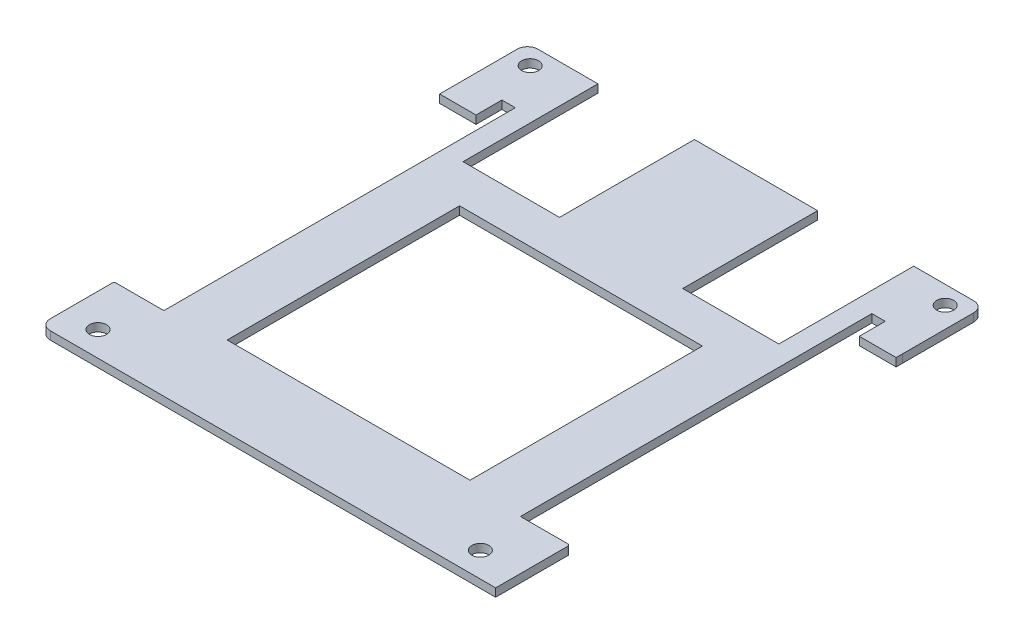
SolidWorks part; units mm, degrees
material "Copper"
ref_plane "Front Plane" through (0, 0, 0) normal (0, 0, 1) x (1, 0, 0)
ref_plane "Top Plane" through (0, 0, 0) normal (0, 1, 0) x (1, 0, 0)
ref_plane "Right Plane" through (0, 0, 0) normal (1, 0, 0) x (0, 0, -1)
sketch "Sketch1" plane through (0, 0, 0) normal (0, 1, 0) x (1, 0, 0)
  line L0 (-44, 45) -> (-44, 29.1624)
  line L1 (-43.6121, 28.7745) -> (-33.2119, 28.7745)
  line L2 (-42, 47) -> (42, 47)
  line L3 (44, 45) -> (44, 31.284)
  line L4 (32.8228, 27.7745) -> (32.8228, -30.4694)
  line L5 (26.2188, 17.9319) -> (-33.6927, 17.9319) construction
  line L6 (33.8228, 28.7745) -> (43.6111, 28.7745)
  line L7 (43.8497, -38.27) -> (43.8497, -47)
  line L8 (42.7059, -47) -> (-42, -47)
  line L9 (-44, -45) -> (-44, -38.977)
  line L10 (-32.824, 28.3866) -> (-32.824, -32.3056)
  line L11 (33.824, -32.6935) -> (36.0988, -32.6935)
  line L12 (23.409, -31.5) -> (-23.409, -31.5)
  line L13 (-23.409, -31.5) -> (-23.409, 13.2954)
  line L14 (-23.409, 13.2954) -> (-12.909, 13.2954)
  line L15 (-12.909, 13.2954) -> (-12.909, 25.9954)
  line L16 (-12.909, 25.9954) -> (12.909, 25.9954)
  line L17 (12.909, 25.9954) -> (12.909, 13.2954)
  line L18 (12.909, 13.2954) -> (23.409, 13.2954)
  line L19 (23.409, 13.2954) -> (23.409, -31.5)
  line L20 (43.8497, -38.27) -> (43.8497, -33.0814)
  line L21 (43.4618, -32.6935) -> (36.0988, -32.6935)
  line L22 (43.8497, -47) -> (42.7059, -47)
  line L23 (-44, 28.7745) -> (52.9697, 28.7745) construction
  line L24 (44, 31.284) -> (43.999, 29.1622)
  line L25 (-33.2119, -32.6935) -> (-36.1, -32.6935)
  line L26 (-44, -38.977) -> (-44, -33.0814)
  line L27 (-43.6121, -32.6935) -> (-36.1, -32.6935)
  line L28 (32.8228, -30.4694) -> (32.8228, -32.6935)
  line L29 (32.8228, -32.6935) -> (33.824, -32.6935)
  circle A0 centre (40, 43.5) radius 1.6383
  circle A1 centre (-40, 43.5) radius 1.6383
  circle A2 centre (-37.6, -42.2) radius 1.6383
  circle A3 centre (36.1, -42.2) radius 1.6383
  arc A5 (-42, 47) -> (-44, 45) centre (-42, 45) ccw
  arc A6 (44, 45) -> (42, 47) centre (42, 45) ccw
  arc A7 (-32.824, -32.3056) -> (-33.2119, -32.6935) centre (-33.2119, -32.3056) cw
  arc A10 (-33.2119, 28.7745) -> (-32.824, 28.3866) centre (-33.2119, 28.3866) cw
  arc A11 (-44, -45) -> (-42, -47) centre (-42, -45) ccw
  arc A12 (-44, 29.1624) -> (-43.6121, 28.7745) centre (-43.6121, 29.1624) ccw
  arc A13 (43.999, 29.1622) -> (43.6111, 28.7745) centre (43.6111, 29.1624) cw
  arc A14 (43.8497, -33.0814) -> (43.4618, -32.6935) centre (43.4618, -33.0814) ccw
  arc A15 (-44, -33.0814) -> (-43.6121, -32.6935) centre (-43.6121, -33.0814) cw
  arc A16 (33.8228, 28.7745) -> (32.8228, 27.7745) centre (33.8228, 27.7745) ccw
  point P27 (32.8228, -32.6935)
  point P51 (-32.824, -32.6935)
  point P54 (-32.824, 28.7745)
  point P60 (43.9988, 28.7745)
  point P67 (32.8228, 28.7745)
  dimension "D24" = 61.468
  dimension "D3" = 80
  dimension "D8" = 3.2766
  dimension "D22" = 1
  dimension "D2" = 6.4
  dimension "D4" = 44.7954
  dimension "D5" = 12.7
  dimension "D6" = 44.7954
  dimension "D7" = 3.5
  dimension "D9" = 4
  dimension "D10" = 3.5
  dimension "D11" = 85.7
  dimension "D12" = 85.7
  dimension "D13" = 21.0046
  dimension "D14" = 11.176
  dimension "D15" = 84
  dimension "D16" = 25.818
  dimension "D17" = 12.7
  dimension "D18" = 46.818
  dimension "D19" = 10.5
  dimension "D20" = 10.5
  dimension "D21" = 73.7
  dimension "D23" = 13.716
  dimension "D26" = 6.604
  dimension "D29" = 11.176
  dimension "D30" = 61.468
  dimension "D31" = 3.276
  dimension "D32" = 3.276
extrude "Boss-Extrude1" add sketch "Sketch1" along normal blind 1.575
sketch "Sketch2" plane through (0, 1.575, 0) normal (0, 1, 0) x (1, 0, 0)
  line L0 (-12.909, 19.06) -> (-30.435, 19.06)
  line L1 (42, 47) -> (-42, 47) construction
  line L2 (-12.909, 25.9954) -> (12.909, 25.9954) construction
  line L3 (-30.435, 47) -> (30.435, 47)
  line L4 (12.909, 13.2954) -> (12.909, 25.9954) construction
  line L5 (12.909, 19.06) -> (30.435, 19.06)
  line L6 (30.435, 19.06) -> (30.435, 47)
  line L7 (0, 47) -> (0, -47) construction
  line L8 (-42, -47) -> (43.8497, -47) construction
  line L9 (-12.909, 25.9954) -> (-12.909, 19.06)
  line L10 (-30.435, 19.06) -> (-30.435, 47)
  line L11 (12.909, 25.9954) -> (12.909, 19.06)
  line L13 (-12.909, 25.9954) -> (12.909, 25.9954)
  dimension "D1" = 27.94
  dimension "D2" = 17.526
extrude "Cut-Extrude1" cut sketch "Sketch2" against normal blind 2.54
sketch "Sketch16" plane through (0, 1.575, 0) normal (0, 1, 0) x (1, 0, 0)
  line L0 (-42, 47) -> (42, 47) construction
  line L1 (12.909, 19.06) -> (12.909, 13.2954)
  line L2 (12.909, 13.2954) -> (-12.909, 13.2954)
  line L3 (-11.8389, 47) -> (-11.8389, 21)
  line L4 (-30.435, 21) -> (-11.8389, 21)
  line L5 (11.909, 21) -> (11.909, 47)
  line L6 (11.909, 47) -> (-11.8389, 47)
  line L7 (-30.435, 47) -> (-30.435, 19.06) construction
  line L9 (-12.909, 19.06) -> (-12.909, 13.2954)
  line L10 (-30.435, 47) -> (-42, 47) construction
  line L11 (11.909, 21) -> (30.435, 21)
  line L12 (30.435, 19.06) -> (30.435, 47) construction
  line L13 (30.435, 21) -> (30.435, 19.06)
  line L14 (30.435, 19.06) -> (12.909, 19.06)
  line L15 (-30.435, 21) -> (-30.435, 19.06)
  line L16 (-30.435, 19.06) -> (-12.909, 19.06)
  dimension "D1" = 26
extrude "Cutouts for Thruster Heads" add sketch "Sketch16" against normal blind 1.575
sketch "Sketch17" plane through (0, 1.575, 0) normal (0, 1, 0) x (1, 0, 0)
  line L2 (-42.6204, -10.5244) -> (-42.6204, -23.1918)
  line L3 (-42.6204, -23.1918) -> (43.1801, -23.1918)
  line L4 (43.1801, -10.5244) -> (43.1801, -23.1918)
  line L6 (-42.6204, -10.5244) -> (-42.6204, 5.0143)
  line L7 (-42.6204, 5.0143) -> (43.1801, 5.0143)
  line L8 (43.1801, -10.5244) -> (43.1801, 5.0143)
sketch "Sketch18" plane through (0, 1.575, 0) normal (0, 1, 0) x (1, 0, 0)
  line L1 (33.4307, -29.0671) -> (45.3514, -29.0671)
  line L2 (33.4307, -29.0671) -> (33.4307, -32.653)
  line L3 (33.4307, -32.653) -> (45.3514, -32.653)
  line L4 (45.3514, -29.0671) -> (45.3514, -32.653)
  dimension "D1" = 14.347
  dimension "D2" = 10.419
sketch "Sketch21" [suppressed] plane through (0, 1.575, 0) normal (0, 1, 0) x (1, 0, 0)
  line L0 (-32.824, 28.3866) -> (-32.824, -32.3056) construction
  line L1 (-32.824, -23.1918) -> (32.8228, -23.1918)
  line L2 (-32.824, -23.1918) -> (-32.824, -25.8658)
  line L3 (-32.824, -25.8658) -> (32.8228, -25.8658)
  line L4 (32.8228, -23.1918) -> (32.8228, -25.8658)
  dimension "D1" = 2.674
sketch "Sketch20" plane through (0, 1.575, 0) normal (0, 1, 0) x (1, 0, 0)
sketch "Notch for BPR (TOP VIEW)" plane through (0, 1.575, 0) normal (0, 1, 0) x (1, 0, 0)
  line L0 (-43.6121, 28.7745) -> (-33.2119, 28.7745) construction
  line L1 (-36.984, 35.0445) -> (-34.409, 35.0445)
  line L2 (-36.984, 35.0445) -> (-36.984, 28.7745)
  line L3 (-36.984, 28.7745) -> (-34.409, 28.7745)
  line L4 (-34.409, 35.0445) -> (-34.409, 28.7745)
  line L6 (-44, 45) -> (-44, 29.1624) construction
  dimension "D1" = 7.016
  dimension "D2" = 2.575
  dimension "D3" = 6.27
extrude "Cut-Extrude11" cut sketch "Notch for BPR (TOP VIEW)" against normal blind 10
sketch "Notch for BPL (TOP VIEW)" plane through (0, 1.575, 0) normal (0, 1, 0) x (1, 0, 0)
  line L0 (33.8228, 28.7745) -> (43.6111, 28.7745) construction
  line L1 (34.3242, 35.0445) -> (36.8992, 35.0445)
  line L2 (34.3242, 35.0445) -> (34.3242, 28.7745)
  line L3 (34.3242, 28.7745) -> (36.8992, 28.7745)
  line L4 (36.8992, 35.0445) -> (36.8992, 28.7745)
  line L5 (44, 31.284) -> (44, 45) construction
  dimension "D1" = 2.575
  dimension "D2" = 7.1008
extrude "Cut-Extrude12" cut sketch "Notch for BPL (TOP VIEW)" against normal through all
sketch "Sketch22" plane through (0, 1.575, 0) normal (0, 1, 0) x (1, 0, 0)
  line L0 (-32.824, -32.3056) -> (-32.824, -38.5911) construction
  line L1 (34.3242, 28.7745) -> (32.8228, 28.7745)
  line L2 (34.3242, 28.7745) -> (34.3242, -32.6935)
  line L3 (34.3242, -32.6935) -> (32.8228, -32.6935)
  line L4 (32.8228, 28.7745) -> (32.8228, -32.6935)
  line L5 (-33.2119, -32.6935) -> (-31.5595, -32.6935) construction
  line L7 (-32.824, -32.6935) -> (-34.409, -32.6935)
  line L8 (-32.824, -32.6935) -> (-32.824, 28.7745)
  line L9 (-32.824, 28.7745) -> (-34.409, 28.7745)
  line L10 (-34.409, -32.6935) -> (-34.409, 28.7745)
extrude "Boss-Extrude2" add sketch "Sketch22" against normal blind 1.575
sketch "Sketch23" plane through (0, 1.575, 0) normal (0, 1, 0) x (1, 0, 0)
  line L0 (43.999, 29.1622) -> (44, 31.284) construction
  line L1 (36.8992, 28.7745) -> (43.9994, 28.7745)
  line L2 (36.8992, 28.7745) -> (36.8992, 30.0445)
  line L3 (36.8992, 30.0445) -> (43.9994, 30.0445)
  line L4 (43.9994, 28.7745) -> (43.9994, 30.0445)
  line L5 (-44, 45) -> (-44, 29.1624) construction
  line L6 (-36.984, 28.7745) -> (-44, 28.7745)
  line L7 (-36.984, 28.7745) -> (-36.984, 30.0445)
  line L8 (-36.984, 30.0445) -> (-44, 30.0445)
  line L9 (-44, 28.7745) -> (-44, 30.0445)
  dimension "D1" = 1.27
  dimension "D2" = 1.27
extrude "Cut-Extrude13" cut sketch "Sketch23" against normal through all
